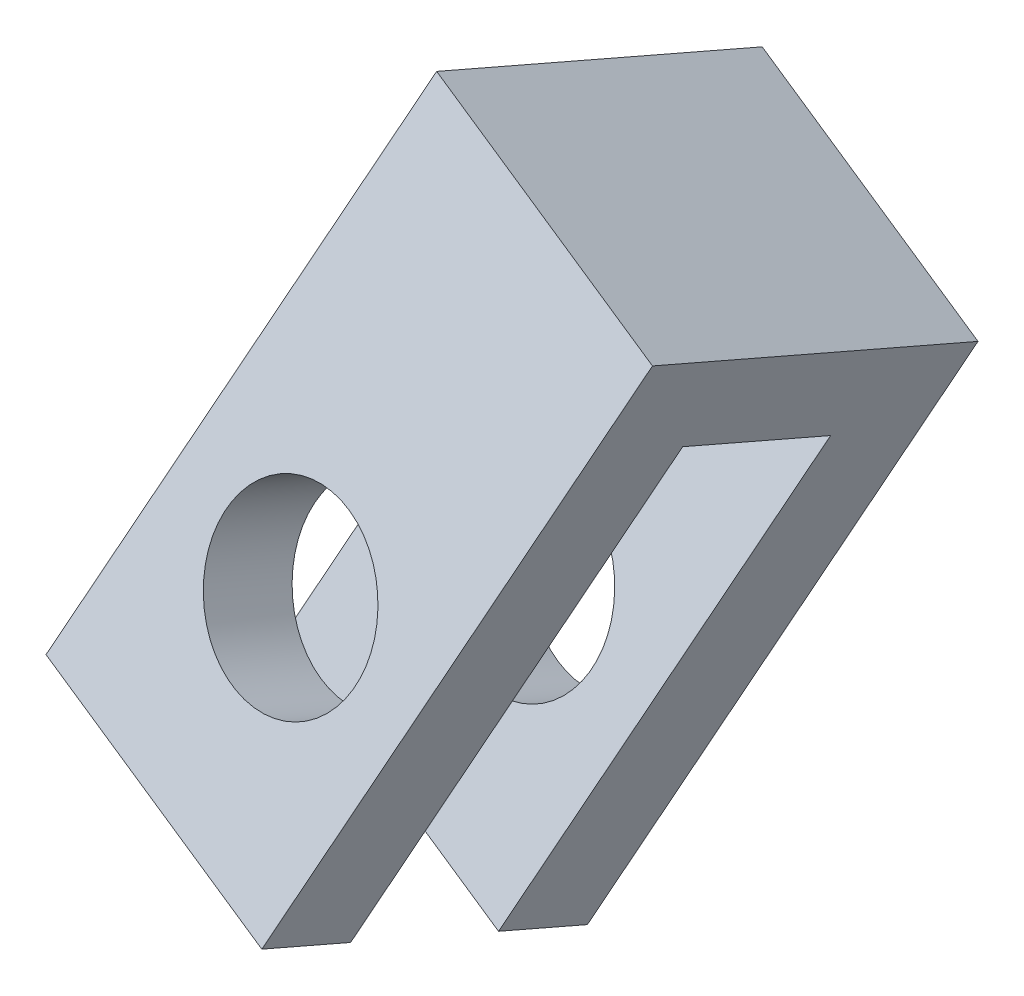
SolidWorks part; units mm, degrees
ref_plane "Front Plane" through (0, 0, 0) normal (0, 0, 1) x (1, 0, 0)
ref_plane "Top Plane" through (0, 0, 0) normal (0, 1, 0) x (1, 0, 0)
ref_plane "Right Plane" through (0, 0, 0) normal (1, 0, 0) x (0, 0, -1)
sketch "Sketch2" plane through (707.5622, 137.847, -295.1758) normal (-0.9319, 0.3048, -0.1966) x (0.3542, 0.8818, -0.3113)
  line L0 (-166.5458, -35.4961) -> (-149.5458, -35.4961)
  line L1 (-149.5458, -35.4961) -> (-149.5458, -40.4961)
  line L2 (-149.5458, -40.4961) -> (-166.5458, -40.4961)
  line L3 (-166.5458, -40.4961) -> (-166.5458, -43.4961)
  line L4 (-166.5458, -43.4961) -> (-146.5458, -43.4961)
  line L5 (-146.5458, -43.4961) -> (-146.5458, -32.4961)
  line L6 (-146.5458, -32.4961) -> (-166.5458, -32.4961)
  line L7 (-166.5458, -32.4961) -> (-166.5458, -35.4961)
  dimension "D1" = 5
  dimension "D2" = 3
  dimension "D3" = 3
  dimension "D4" = 20
  dimension "D5" = 3
  dimension "D6" = 20
extrude "Boss-Extrude1" add sketch "Sketch2" along normal blind 10 contours L4 L5 L6 L7 L0 L1 L2 L3
sketch "Sketch3" plane through (18.8265, -86.3012, -223.022) normal (0.0785, -0.3598, -0.9297) x (-0.9969, -0.0283, -0.0732)
  line L0 (-625.2036, 98.844) -> (-619.1642, 82.9529) construction
  line L2 (-619.1642, 82.9529) -> (-628.5119, 79.4003) construction
  circle A0 centre (-626.3249, 87.72) radius 3
  dimension "D1" = 6
  dimension "D2" = 5
  dimension "D3" = 7
extrude "Cut-Extrude1" cut sketch "Sketch3" against normal through all both and the other way through all contours A0
